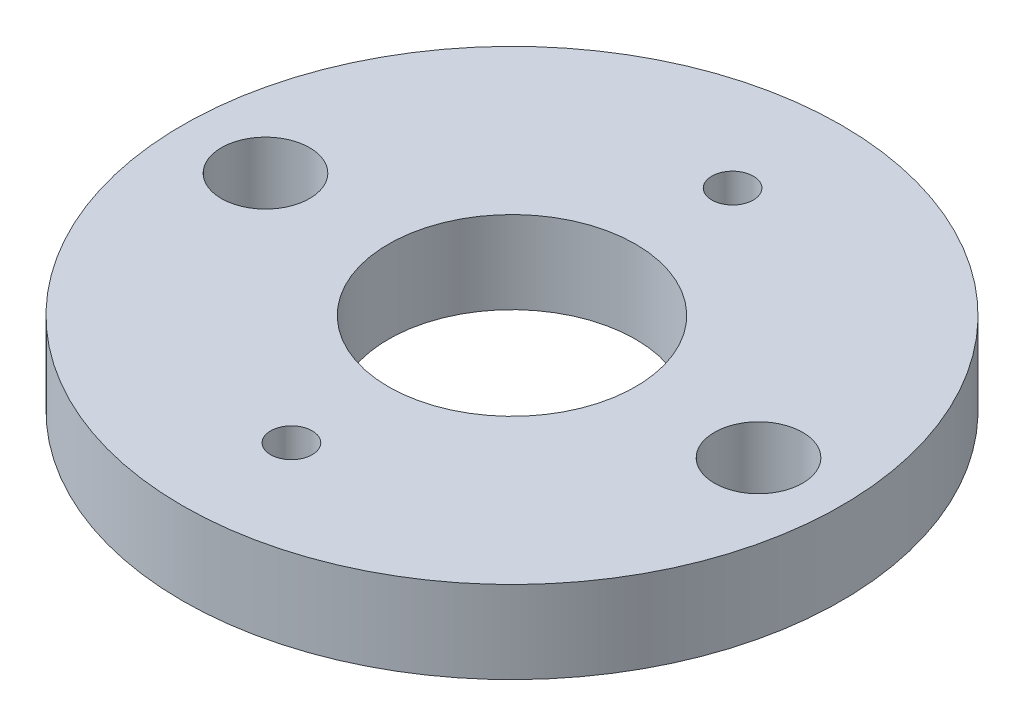
SolidWorks part; units mm, degrees
ref_plane "Front Plane" through (0, 0, 0) normal (0, 0, 1) x (1, 0, 0)
ref_plane "Top Plane" through (0, 0, 0) normal (0, 1, 0) x (1, 0, 0)
ref_plane "Right Plane" through (0, 0, 0) normal (1, 0, 0) x (0, 0, -1)
sketch "Sketch1" plane through (0, 0, 0) normal (0, 1, 0) x (1, 0, 0)
  circle A0 centre (0, 0) radius 12.7
  circle A1 centre (0, 0) radius 4.7625
  dimension "D1" = 25.4
  dimension "D2" = 9.525
extrude "Boss-Extrude1" add sketch "Sketch1" along normal blind 3.175
sketch "Sketch2" plane through (0, 3.175, 0) normal (0, 1, 0) x (1, 0, 0)
  line L0 (-9.5, 0) -> (9.5, 0)
  line L1 (0, -8.5) -> (0, 8.5)
  point P4 (0, 0)
  point P8 (0, 0)
  dimension "D1" = 17
  dimension "D2" = 19
hole_wizard "M3 Clearance Hole1" positions "Sketch3" profile "Sketch4" hole size "M3" standard "ANSI Metric"
sketch "Sketch3" plane through (0, 3.175, 0) normal (0, 1, 0) x (1, 0, 0)
  point P0 (-9.5, 0)
  point P3 (9.5, 0)
sketch "Sketch4" plane through (-9.5, 3.175, 0) normal (1, 0, 0) x (0, 0, 1)
  line L0 (0, 0) -> (0, 7.3715)
  line L1 (0, 7.3715) -> (1.7, 6.35)
  line L2 (1.7, 6.35) -> (1.7, 0)
  line L5 (1.7, 0) -> (0, 0)
  line L10 (0, 7.3715) -> (-1.7, 6.35) construction
  line L11 (0, -6.35) -> (0, 107.95) construction
  dimension "Hole Dia." = 3.4
  dimension "Hole Depth" = 6.35
  dimension "Drill Angle" = 118
hole_wizard "Tap Drill for M2x0.4 Tap1" positions "Sketch5" profile "Sketch6" hole size "M2x0.4" standard "ANSI Metric"
sketch "Sketch5" plane through (0, 3.175, 0) normal (0, 1, 0) x (1, 0, 0)
  point P0 (0, 8.5)
  point P3 (0, -8.5)
sketch "Sketch6" plane through (0, 3.175, -8.5) normal (1, 0, 0) x (0, 0, 1)
  line L0 (0, 0) -> (0, 6.8307)
  line L1 (0, 6.8307) -> (0.8, 6.35)
  line L2 (0.8, 6.35) -> (0.8, 0)
  line L5 (0.8, 0) -> (0, 0)
  line L10 (0, 6.8307) -> (-0.8, 6.35) construction
  line L11 (0, -6.35) -> (0, 107.95) construction
  dimension "Hole Dia." = 1.6
  dimension "Hole Depth" = 6.35
  dimension "Drill Angle" = 118
